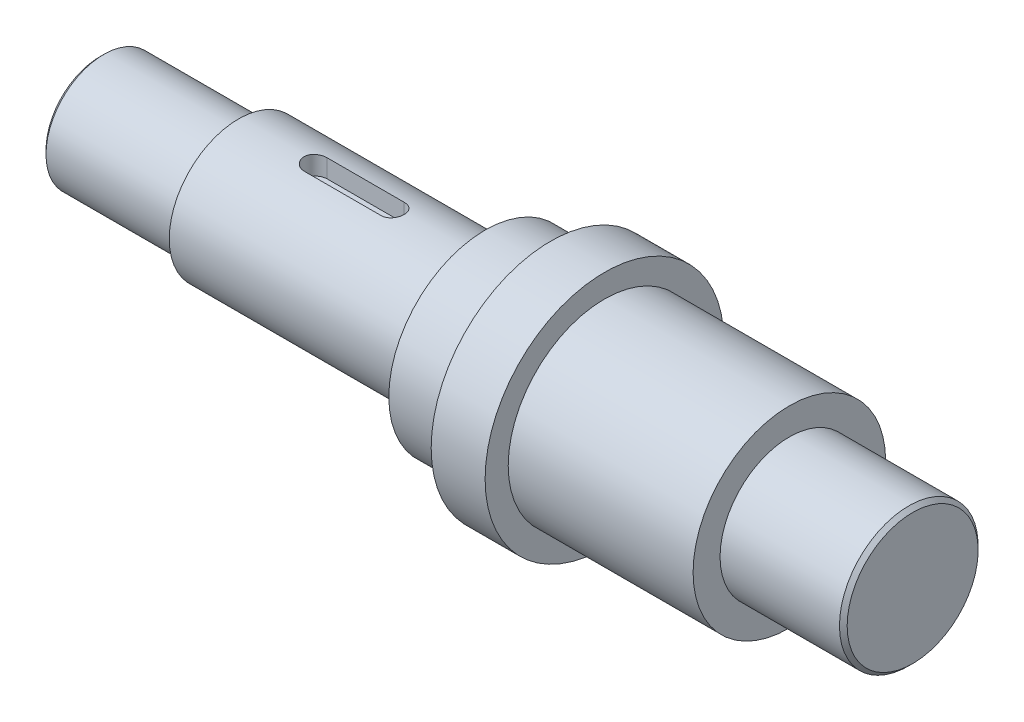
SolidWorks part; units mm, degrees
material "普通碳钢"
ref_plane "前视基准面" through (0, 0, 0) normal (0, 0, 1) x (1, 0, 0)
ref_plane "上视基准面" through (0, 0, 0) normal (0, 1, 0) x (1, 0, 0)
ref_plane "右视基准面" through (0, 0, 0) normal (1, 0, 0) x (0, 0, -1)
other "Configuration Table"
sketch "草图1" plane through (0, 0, 0) normal (0, 0, 1) x (1, 0, 0)
  line L0 (0, 0) -> (0, 7)
  line L1 (0, 7) -> (0.5, 7.5)
  line L2 (0.5, 7.5) -> (18, 7.5)
  line L3 (18, 7.5) -> (18, 9)
  line L4 (18, 9) -> (50, 9)
  line L5 (50, 9) -> (50, 12.5)
  line L6 (50, 12.5) -> (58.5, 12.5)
  line L7 (58.5, 12.5) -> (58.5, 15.5)
  line L8 (58.5, 15.5) -> (65.5, 15.5)
  line L9 (65.5, 15.5) -> (65.5, 12.5)
  line L10 (65.5, 12.5) -> (89.5, 12.5)
  line L11 (89.5, 12.5) -> (89.5, 9)
  line L12 (89.5, 9) -> (105, 9)
  line L13 (105, 9) -> (105.5, 8.5)
  line L14 (105.5, 8.5) -> (105.5, 0)
  line L15 (105.5, 0) -> (0, 0)
  line L16 (-5, 0) -> (110, 0) construction
revolve "旋转1" add sketch "草图1" angle 360 about L16
ref_plane "Plane_Keyway" through (0, 9, 0) normal (0, 1, 0) x (1, 0, 0)
sketch "草图2" plane through (0, 9, 0) normal (0, 1, 0) x (1, 0, 0)
  line L0 (28, 0) -> (38, 0) construction
  line L1 (28, 1.5) -> (38, 1.5)
  line L2 (28, -1.5) -> (38, -1.5)
  arc A0 (28, 1.5) -> (28, -1.5) centre (28, 0) ccw
  arc A1 (38, -1.5) -> (38, 1.5) centre (38, 0) ccw
  point P3 (33, 0)
extrude "02_KEYWAY" cut sketch "草图2" against normal blind 2.5
